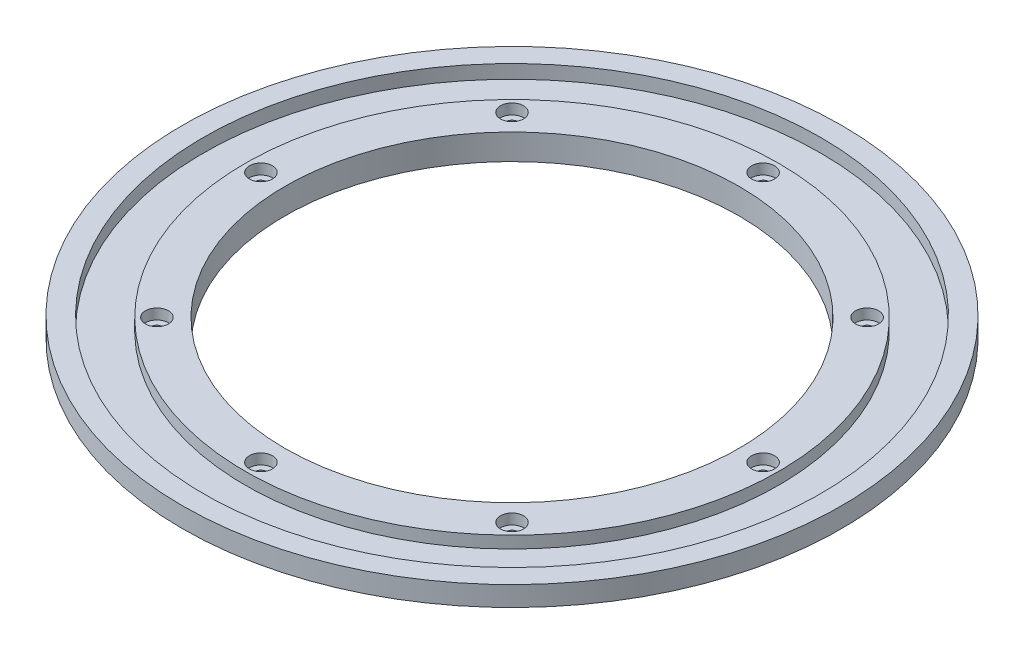
SolidWorks part; units mm, degrees
ref_plane "Front Plane" through (0, 0, 0) normal (0, 0, 1) x (1, 0, 0)
ref_plane "Top Plane" through (0, 0, 0) normal (0, 1, 0) x (1, 0, 0)
ref_plane "Right Plane" through (0, 0, 0) normal (1, 0, 0) x (0, 0, -1)
sketch "Sketch3" plane through (0, 0, 0) normal (1, 0, 0) x (0, 0, -1)
  line L0 (0, -1465.1364) -> (0, 71791.6854) construction
  line L1 (-315, 34.7123) -> (-295, 34.7123)
  line L2 (-295, 34.7123) -> (-295, 21.7123)
  line L3 (-295, 21.7123) -> (-255, 21.7123)
  line L4 (-255, 21.7123) -> (-255, 33.2123)
  line L5 (-255, 33.2123) -> (-217, 33.2123)
  line L6 (-217, 33.2123) -> (-217, 8.7123)
  line L9 (-229, 15.7123) -> (-315, 15.7123)
  line L10 (-315, 15.7123) -> (-315, 34.7123)
  line L11 (-217, 8.7123) -> (-229, 8.7123)
  line L12 (-229, 8.7123) -> (-229, 15.7123)
  dimension "D1" = 19
  dimension "D3" = 24.5
  dimension "D4" = 38
  dimension "D5" = 40
  dimension "D6" = 13
  dimension "D8" = 20
  dimension "D9" = 510
  dimension "D10" = 590
  dimension "D11" = 6
revolve "Revolve1" add sketch "Sketch3" angle 360 about L0
sketch "Sketch4" plane through (0, 33.2123, 0) normal (0, 1, 0) x (1, 0, 0)
  line L0 (0, -1000) -> (0, 49000) construction
  line L1 (-1000, 0) -> (49000, 0) construction
  circle A0 centre (0, 240) radius 5
  circle A1 centre (0, 0) radius 217 construction
  circle A2 centre (169.7056, 169.7056) radius 5
  circle A3 centre (240, 0) radius 5
  circle A4 centre (169.7056, -169.7056) radius 5
  circle A5 centre (0, -240) radius 5
  circle A6 centre (-169.7056, -169.7056) radius 5
  circle A7 centre (-240, 0) radius 5
  circle A8 centre (-169.7056, 169.7056) radius 5
  point P27 (0, 0)
  dimension "D1" = 10
  dimension "D2" = 240
  dimension "D3" = 8
extrude "Cut-Extrude1" cut sketch "Sketch4" against normal through all
sketch "Sketch5" plane through (0, 33.2123, 0) normal (0, 1, 0) x (1, 0, 0)
  circle A0 centre (0, 240) radius 11
  circle A1 centre (169.7056, 169.7056) radius 11
  circle A2 centre (240, 0) radius 11
  circle A3 centre (169.7056, -169.7056) radius 11
  circle A4 centre (0, -240) radius 11
  circle A5 centre (-169.7056, -169.7056) radius 11
  circle A6 centre (-240, 0) radius 11
  circle A7 centre (-169.7056, 169.7056) radius 11
  point P19 (0, 0)
  dimension "D1" = 8
extrude "Cut-Extrude2" cut sketch "Sketch5" against normal blind 10
